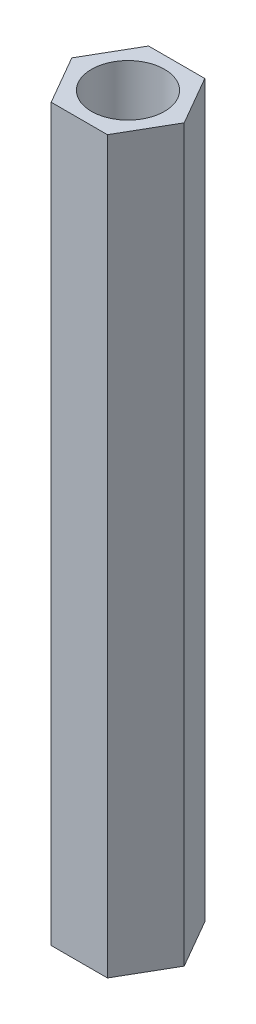
SolidWorks part; units mm, degrees
ref_plane "Front Plane" through (0, 0, 0) normal (0, 0, 1) x (1, 0, 0)
ref_plane "Top Plane" through (0, 0, 0) normal (0, 1, 0) x (1, 0, 0)
ref_plane "Right Plane" through (0, 0, 0) normal (1, 0, 0) x (0, 0, -1)
sketch "草图1" plane through (0, 0, 0) normal (0, 1, 0) x (1, 0, 0)
  line L1 (2.3094, 0) -> (1.1547, 2)
  line L2 (1.1547, 2) -> (-1.1547, 2)
  line L3 (-1.1547, 2) -> (-2.3094, 0)
  line L4 (-2.3094, 0) -> (-1.1547, -2)
  line L5 (-1.1547, -2) -> (1.1547, -2)
  line L6 (1.1547, -2) -> (2.3094, 0)
  circle A0 centre (0, 0) radius 2 construction
  dimension "D1" = 4
extrude "凸台-拉伸1" add sketch "草图1" along normal blind 30
sketch "草图2" plane through (0, 30, 0) normal (0, 1, 0) x (1, 0, 0)
  circle A0 centre (0, 0) radius 1.5
  dimension "D1" = 3
extrude "切除-拉伸1" cut sketch "草图2" against normal through all
